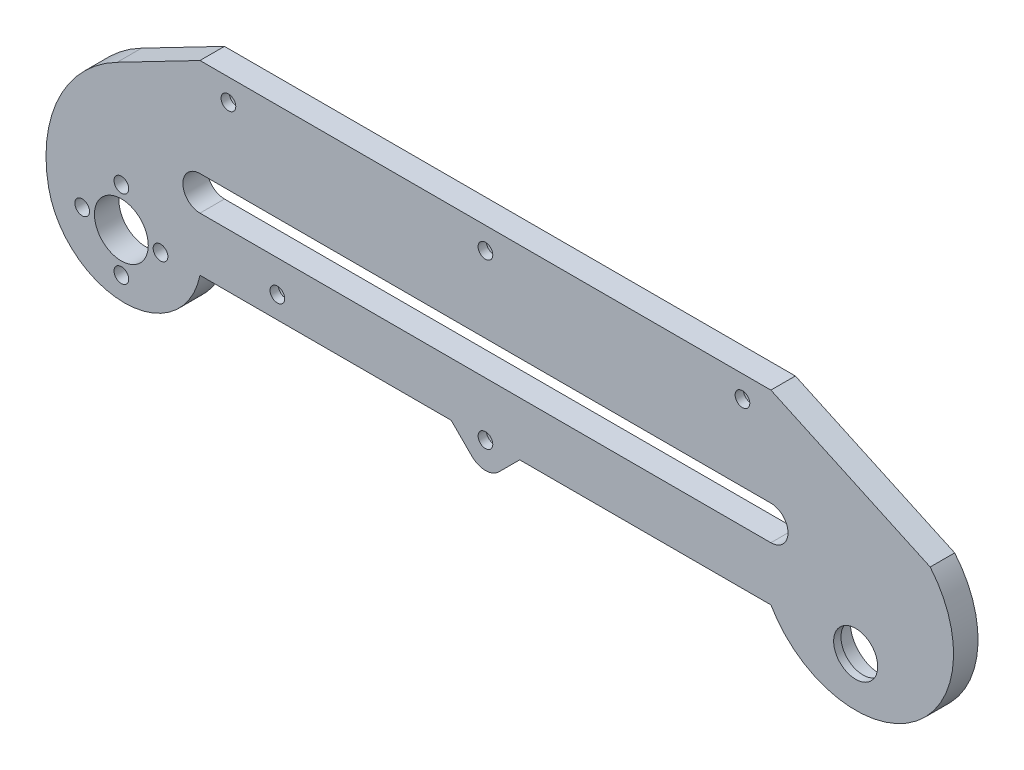
SolidWorks part; units mm, degrees
ref_plane "Front Plane" through (0, 0, 0) normal (0, 0, 1) x (1, 0, 0)
ref_plane "Top Plane" through (0, 0, 0) normal (0, 1, 0) x (1, 0, 0)
ref_plane "Right Plane" through (0, 0, 0) normal (1, 0, 0) x (0, 0, -1)
sketch "Sketch1" plane through (0, 0, 0) normal (0, 0, 1) x (1, 0, 0)
  line L0 (-58.3087, -15) -> (-89.2173, -15) construction
  line L5 (-74.3708, 5.1315) -> (-74.3708, -26.8454) construction
  line L6 (58.3087, -15) -> (75.6292, -15) construction
  line L7 (-58.3087, -4.0039) -> (58.3087, -4.0039)
  line L8 (58.3087, -0.5039) -> (58.3087, -15) construction
  line L9 (-58.3087, 2.9961) -> (58.3087, 2.9961)
  line L10 (-58.3087, 22.9961) -> (58.3087, 22.9961)
  line L11 (75.6292, -5) -> (75.6292, 15) construction
  line L12 (-58.3087, -15) -> (-58.3087, -4.0039) construction
  line L13 (75.6292, 15) -> (58.3087, 22.9961)
  line L14 (75.6292, -15) -> (75.6292, -10.5) construction
  line L15 (75.6292, -15) -> (75.6292, -5) construction
  line L16 (-58.3087, 22.9961) -> (-75.2437, 14.2129)
  line L17 (-58.3087, -15) -> (-7, -15)
  line L19 (58.3087, -15) -> (7, -15)
  line L20 (0, -15.0039) -> (0, -4.0039) construction
  line L23 (-7, -15) -> (-2.7574, -19.2426)
  line L24 (7, -15) -> (2.7574, -19.2426)
  line L25 (75.6292, 15) -> (90.8512, 7.9726)
  arc A1 (90.8512, 7.9726) -> (58.3087, -15) centre (75.6292, -5) cw
  circle A2 centre (-74.3708, -15) radius 5.5
  circle A3 centre (-74.3708, -7) radius 1.5
  circle A5 centre (75.6292, -15) radius 4.5
  circle A6 centre (0, -15.0039) radius 1.5
  arc A10 (-58.3087, 2.9961) -> (-58.3087, -4.0039) centre (-58.3087, -0.5039) ccw
  arc A11 (58.3087, 2.9961) -> (58.3087, -4.0039) centre (58.3087, -0.5039) cw
  circle A13 centre (-66.3708, -15) radius 1.5
  circle A14 centre (-74.3708, -23) radius 1.5
  circle A15 centre (-82.3708, -15) radius 1.5
  arc A16 (-58.3087, -15) -> (-89.2173, -15) centre (-73.763, -11.8269) cw
  arc A17 (-89.2173, -15) -> (-75.2437, 14.2129) centre (-62.9636, -9.6096) cw
  arc A18 (-2.7574, -19.2426) -> (2.7574, -19.2426) centre (0, -16.4853) ccw
  point P49 (-74.3708, -15)
  dimension "D1" = 20
  dimension "D2" = 7
  dimension "D3" = 8
  dimension "D5" = 9
  dimension "D6" = 11
  dimension "D9" = 3
  dimension "D10" = 7
  dimension "D4" = 7
  dimension "D7" = 4
  dimension "D8" = 150
  dimension "D11" = 20
  dimension "D12" = 6
  dimension "D13" = 6
  dimension "D14" = 11
extrude "Boss-Extrude1" add sketch "Sketch1" along normal blind 5
ref_plane "Plane1" through (0, 0, 49) normal (0, 0, 1) x (1, 0, 0)
sketch "Sketch2" plane through (0, 0, 49) normal (0, 0, 1) x (1, 0, 0)
  line L2 (-58.3087, -4.0039) -> (58.3087, -4.0039)
  line L3 (58.3087, 2.9961) -> (-58.3087, 2.9961)
  line L4 (-58.3087, -4.0039) -> (58.3087, -4.0039)
  line L5 (58.3087, 2.9961) -> (-58.3087, 2.9961)
  line L8 (90.8512, 7.9726) -> (58.3087, 22.9961)
  line L10 (7, -15) -> (58.3087, -15)
  line L11 (58.3087, 22.9961) -> (-58.3087, 22.9961)
  line L12 (58.3087, 22.9961) -> (-58.3087, 22.9961)
  line L13 (-58.3087, 22.9961) -> (-75.2437, 14.2129)
  line L14 (-58.3087, 22.9961) -> (-75.2437, 14.2129)
  line L17 (90.8512, 7.9726) -> (58.3087, 22.9961)
  line L21 (7, -15) -> (58.3087, -15)
  line L22 (-58.3087, -15) -> (-7, -15)
  line L23 (-58.3087, -15) -> (-7, -15)
  line L24 (-7, -15) -> (-2.7574, -19.2426)
  line L25 (-7, -15) -> (-2.7574, -19.2426)
  line L26 (2.7574, -19.2426) -> (7, -15)
  line L27 (2.7574, -19.2426) -> (7, -15)
  circle A0 centre (-74.3708, -15) radius 5.5
  circle A1 centre (75.6292, -15) radius 4.5
  arc A2 (-58.3087, 2.9961) -> (-58.3087, -4.0039) centre (-58.3087, -0.5039) ccw
  arc A3 (58.3087, -4.0039) -> (58.3087, 2.9961) centre (58.3087, -0.5039) ccw
  arc A4 (-58.3087, 2.9961) -> (-58.3087, -4.0039) centre (-58.3087, -0.5039) ccw
  arc A5 (58.3087, -4.0039) -> (58.3087, 2.9961) centre (58.3087, -0.5039) ccw
  circle A6 centre (75.6292, -15) radius 4.5
  circle A11 centre (0, -15.0039) radius 1.5
  circle A12 centre (0, -15.0039) radius 1.5
  arc A16 (-2.7574, -19.2426) -> (2.7574, -19.2426) centre (0, -16.4853) ccw
  arc A17 (-89.2173, -15) -> (-58.3087, -15) centre (-73.763, -11.8269) ccw
  arc A18 (58.3087, -15) -> (90.8512, 7.9726) centre (75.6292, -5) ccw
  arc A19 (-89.2173, -15) -> (-58.3087, -15) centre (-73.763, -11.8269) ccw
  arc A23 (-75.2437, 14.2129) -> (-89.2173, -15) centre (-62.9636, -9.6096) ccw
  arc A24 (-75.2437, 14.2129) -> (-89.2173, -15) centre (-62.9636, -9.6096) ccw
  arc A26 (58.3087, -15) -> (90.8512, 7.9726) centre (75.6292, -5) ccw
  arc A27 (-2.7574, -19.2426) -> (2.7574, -19.2426) centre (0, -16.4853) ccw
  dimension "D3" = 11
  dimension "D1" = 0
  dimension "D2" = 0
  dimension "D5" = 0
  dimension "D7" = 0
sketch "Sketch4" plane through (0, 0, 0) normal (0, 0, -1) x (-1, 0, 0)
  circle A0 centre (-75.6292, -15) radius 6.1
  dimension "D1" = 12.2
extrude "Cut-Extrude1" cut sketch "Sketch4" against normal blind 3.5
sketch "Sketch5" plane through (0, 0, 0) normal (0, 0, -1) x (-1, 0, 0)
  line L0 (0, -15.0039) -> (0, 22.9961) construction
  line L1 (-58.3087, 22.9961) -> (58.3087, 22.9961) construction
  line L2 (-52.5, 18.4961) -> (52.5, 18.4961) construction
  circle A0 centre (0, 18.4961) radius 1.5
  circle A1 centre (52.5, 18.4961) radius 1.5
  circle A2 centre (-52.5, 18.4961) radius 1.5
  point P10 (0, 18.4961)
  dimension "D1" = 3
  dimension "D2" = 4.5
  dimension "D3" = 105
extrude "Cut-Extrude2" cut sketch "Sketch5" against normal blind 5
sketch "Sketch6" plane through (0, 0, 0) normal (0, 0, -1) x (-1, 0, 0)
  line L0 (58.3087, -15) -> (7, -15) construction
  circle A0 centre (42.5, -10.5) radius 1.5
  circle A1 centre (0, -15.0039) radius 1.5 construction
  dimension "D1" = 3
  dimension "D2" = 42.5
  dimension "D3" = 4.5
extrude "Cut-Extrude3" cut sketch "Sketch6" against normal blind 10
sketch "Sketch7" plane through (0, 0, 0) normal (0, 0, -1) x (-1, 0, 0)
  circle A0 centre (42.5, -10.5) radius 2.9
  circle A1 centre (0, -15.0039) radius 2.9
  circle A2 centre (0, 18.4961) radius 2.9
  circle A3 centre (52.5, 18.4961) radius 2.9
  circle A4 centre (-52.5, 18.4961) radius 2.9
  dimension "D1" = 5.8
  dimension "D2" = 5.8
extrude "Cut-Extrude4" cut sketch "Sketch7" against normal blind 3.3
